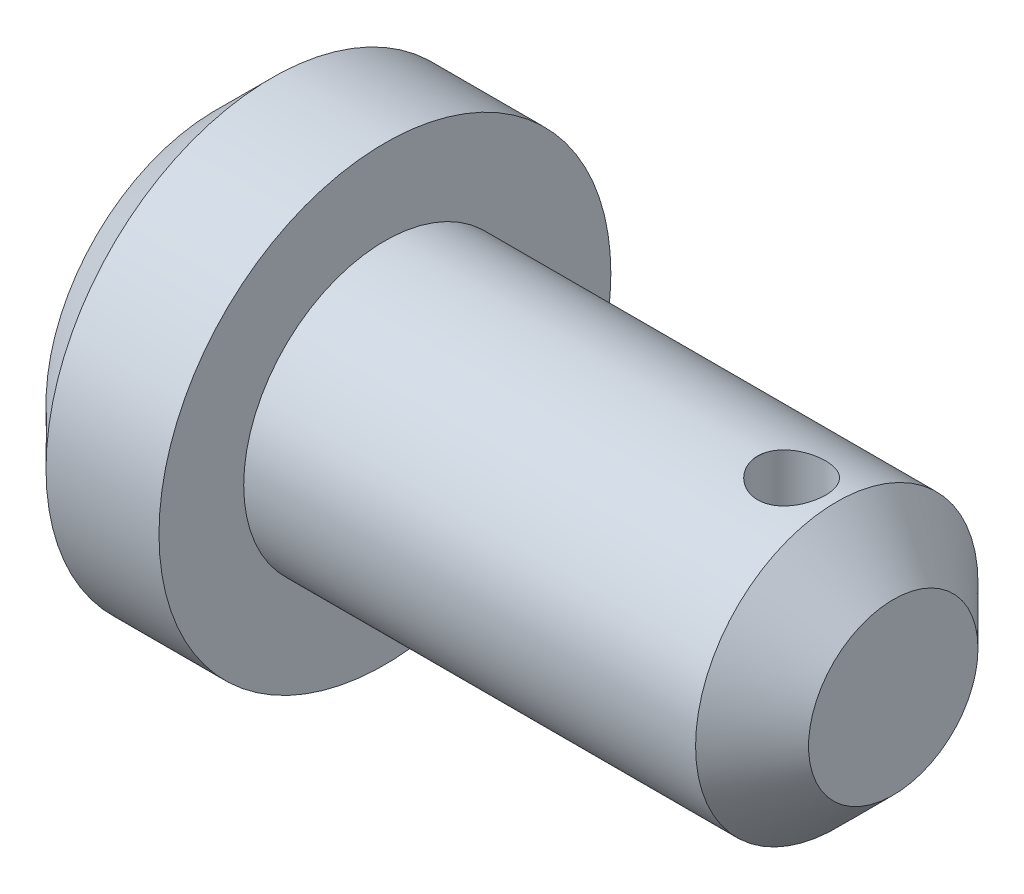
SolidWorks part; units mm, degrees
ref_plane "Front Plane" through (0, 0, 0) normal (1, 0, 0) x (0, 1, 0)
ref_plane "Top Plane" through (0, 0, 0) normal (0, 0, 1) x (0, 1, 0)
ref_plane "Right Plane" through (0, 0, 0) normal (0, 1, 0) x (-1, 0, 0)
sketch "Sketch2" plane through (0, 0, 0) normal (1, 0, 0) x (0, 1, 0)
  circle A0 centre (0, 0) radius 40
  dimension "D1" = 80
extrude "Boss-Extrude1" add sketch "Sketch2" along normal mid plane 120
sketch "Sketch3" plane through (60, 0, 0) normal (1, 0, 0) x (0, 1, 0)
  circle A0 centre (0, 0) radius 25
  circle M2 centre (0, 0) radius 40
  dimension "D1" = 50
extrude "Cut-Extrude1" cut sketch "Sketch3" against normal blind 90 contours A0 M2
chamfer "Chamfer1" distance 10 angle 45 2 edges at (-60, 0, -40) (60, 0, -25)
ref_plane "Plane1" through (0, 25, 0) normal (0, 1, 0) x (1, 0, 0)
sketch "Sketch4" plane through (0, 25, 0) normal (0, 1, 0) x (1, 0, 0)
  line L0 (-30, -40) -> (-30, 40) construction
  point P0 (42, 0)
  dimension "D1" = 72
hole_wizard "Ø12.0 (12) Diameter Hole1" positions "Sketch4" profile "Sketch5" hole size "Ø12.0" standard "ISO" end condition through all
sketch "Sketch5" plane through (42, 25, 0) normal (1, 0, 0) x (0, 0, 1)
  line L0 (0, 0) -> (0, 65)
  line L1 (0, 65) -> (6, 65)
  line L2 (6, 65) -> (6, 0.025)
  line L3 (6, 0.025) -> (6.025, 0)
  line L5 (6.025, 0) -> (0, 0)
  line L6 (-6, 0.025) -> (-6.025, 0) construction
  line L11 (0, -6.35) -> (0, 107.95) construction
  dimension "Thru Hole Dia." = 12
  dimension "Thru Hole Depth" = 65
  dimension "Near C'Sink Dia." = 12.05
  dimension "Near C'Sink Angle" = 90
